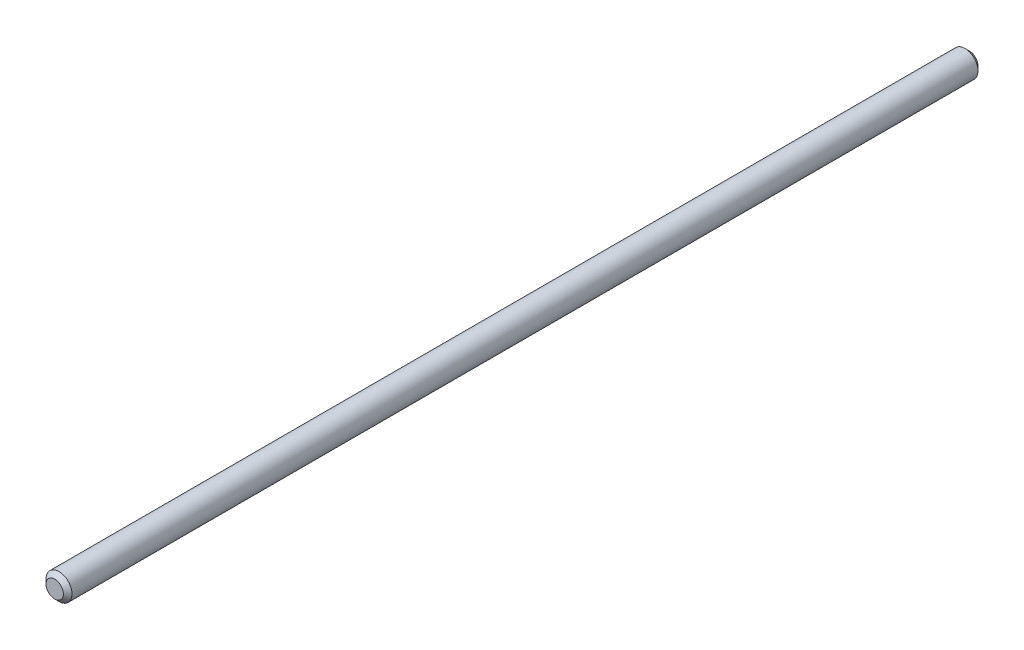
SolidWorks part; units mm, degrees
ref_plane "Face" through (0, 0, 0) normal (0, 0, 1) x (1, 0, 0)
ref_plane "Dessus" through (0, 0, 0) normal (0, 1, 0) x (1, 0, 0)
ref_plane "Droite" through (0, 0, 0) normal (1, 0, 0) x (0, 0, -1)
sketch "Esquisse1" plane through (0, 0, 0) normal (0, 0, 1) x (1, 0, 0)
  circle A0 centre (0, 0) radius 1.5
extrude "Base-Extrusion" add sketch "Esquisse1" along normal mid plane 105.5112
chamfer "Chanfrein1" distance 0.5 angle 45 2 edges at (1.5, 0, -52.7556) (1.5, 0, 52.7556)
ref_point "Point1"
sketch "Esquisse2" plane through (0, 0, 0) normal (1, 0, 0) x (0, 0, -1)
  point P0 (-51.2444, 27.8823)
